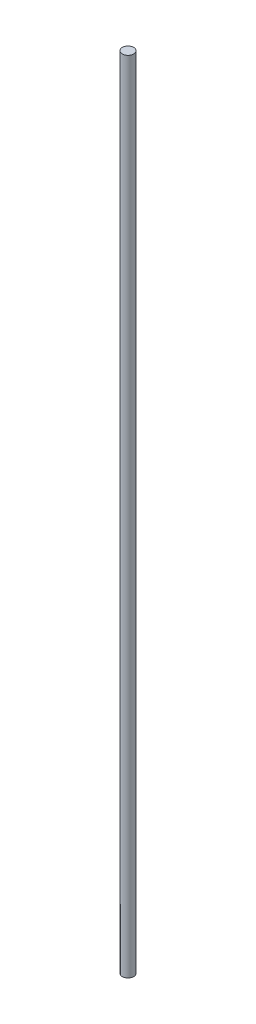
SolidWorks part; units mm, degrees
ref_plane "Front Plane" through (0, 0, 0) normal (0, 0, 1) x (1, 0, 0)
ref_plane "Top Plane" through (0, 0, 0) normal (0, 1, 0) x (1, 0, 0)
ref_plane "Right Plane" through (0, 0, 0) normal (1, 0, 0) x (0, 0, -1)
sketch "Sketch1" plane through (0, 0, 0) normal (0, 1, 0) x (1, 0, 0)
  circle A0 centre (0, 0) radius 1
  dimension "D1" = 2
extrude "Boss-Extrude1" add sketch "Sketch1" along normal blind 140
